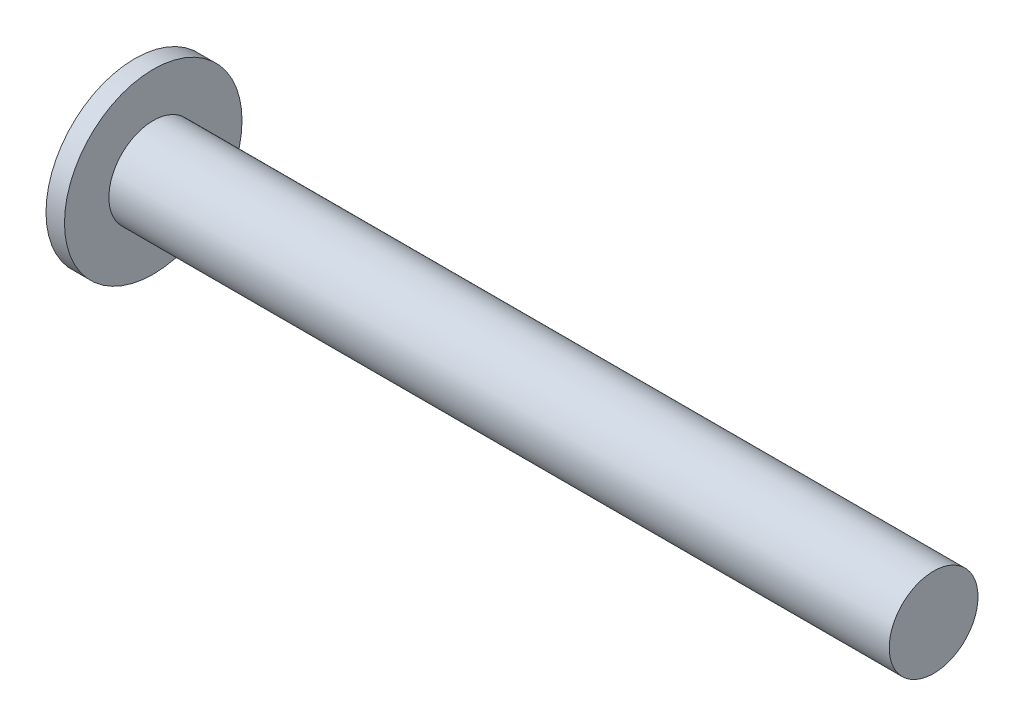
SolidWorks part; units mm, degrees
ref_plane "Спереди" through (0, 0, 0) normal (0, 0, 1) x (1, 0, 0)
ref_plane "Сверху" through (0, 0, 0) normal (0, 1, 0) x (1, 0, 0)
ref_plane "Справа" through (0, 0, 0) normal (1, 0, 0) x (0, 0, -1)
sketch "Эскиз1" plane through (0, 0, 0) normal (1, 0, 0) x (0, 0, -1)
  circle A0 centre (0, 0) radius 12
  dimension "D1" = 24
extrude "Бобышка-Вытянуть1" add sketch "Эскиз1" along normal blind 2.5
sketch "Эскиз2" plane through (2.5, 0, 0) normal (1, 0, 0) x (0, 0, -1)
  circle A0 centre (0, 0) radius 6
  dimension "D1" = 12
extrude "Бобышка-Вытянуть2" add sketch "Эскиз2" along normal blind 105.5
